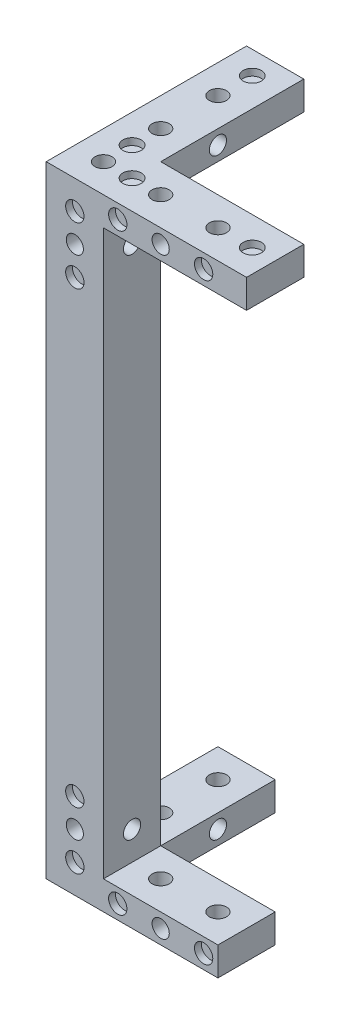
SolidWorks part; units mm, degrees
ref_plane "Front Plane" through (0, 0, 0) normal (0, 0, 1) x (1, 0, 0)
ref_plane "Top Plane" through (0, 0, 0) normal (0, 1, 0) x (1, 0, 0)
ref_plane "Right Plane" through (0, 0, 0) normal (1, 0, 0) x (0, 0, -1)
sketch "Sketch1" plane through (0, 0, 0) normal (0, 1, 0) x (1, 0, 0)
  line L1 (0, 0) -> (30, 0)
  line L2 (0, 0) -> (0, 10)
  line L3 (0, 10) -> (30, 10)
  line L4 (30, 0) -> (30, 10)
  line L5 (0, 0) -> (10, 0)
  line L6 (0, 0) -> (0, 30)
  line L7 (0, 30) -> (10, 30)
  line L8 (10, 0) -> (10, 30)
  dimension "D1" = 10
  dimension "D2" = 10
  dimension "D3" = 30
  dimension "D4" = 30
extrude "Boss-Extrude1" add sketch "Sketch1" along normal blind 10 contours L3 L8 L7 L6 | L1 L8 L3 L2 | L8 L1 L4 L3
sketch "Sketch2" plane through (0, 10, 0) normal (0, 1, 0) x (1, 0, 0)
  line L1 (0, 0) -> (10, 0)
  line L2 (0, 0) -> (0, 10)
  line L3 (0, 10) -> (10, 10)
  line L4 (10, 0) -> (10, 10)
extrude "Boss-Extrude2" add sketch "Sketch2" along normal blind 93.5
sketch "Sketch3" plane through (0, 103.5, 0) normal (0, 1, 0) x (1, 0, 0)
  line L1 (0, 0) -> (30, 0)
  line L2 (0, 0) -> (0, 10)
  line L3 (0, 10) -> (30, 10)
  line L4 (30, 0) -> (30, 10)
  line L5 (0, 0) -> (10, 0)
  line L6 (0, 0) -> (0, 30)
  line L7 (0, 30) -> (10, 30)
  line L8 (10, 0) -> (10, 30)
  line M9 (0, 10) -> (0, 0)
  line M10 (0, 0) -> (10, 0)
  line M11 (10, 0) -> (10, 10)
  line M12 (10, 10) -> (0, 10)
  dimension "D1" = 10
  dimension "D2" = 30
  dimension "D3" = 10
  dimension "D4" = 30
extrude "Boss-Extrude3" add sketch "Sketch3" along normal blind 5 contours L8 L7 L6 M12 | M12 M9 M10 M11 | L1 L4 L3 M11
sketch "Sketch4" plane through (0, 10, 0) normal (0, 1, 0) x (1, 0, 0)
  line L1 (30, 10) -> (10, 10)
  line L2 (30, 10) -> (30, 0)
  line L3 (30, 0) -> (10, 0)
  line L4 (10, 10) -> (10, 0)
  line L5 (10, 30) -> (0, 30)
  line L6 (10, 30) -> (10, 10)
  line L7 (10, 10) -> (0, 10)
  line L8 (0, 30) -> (0, 10)
extrude "Cut-Extrude1" cut sketch "Sketch4" against normal blind 5 contours L5 L8 L7 L6
sketch "Sketch5" plane through (0, 0, 0) normal (0, 0, 1) x (1, 0, 0)
  line L0 (10, 103.5) -> (10, 5) construction
  line L1 (0, 0) -> (30, 0) construction
  line L2 (10, 5) -> (30, 5) construction
  line L3 (30, 5) -> (30, 0) construction
  line L4 (0, 108.5) -> (0, 0) construction
  line L5 (0, 108.5) -> (0, 0)
  line L6 (0, 54.25) -> (10, 54.25)
  circle A0 centre (5, 5) radius 1.6
  circle A1 centre (27.5, 2.5) radius 1.6
  circle A2 centre (5, 15) radius 1.6
  circle A3 centre (12.5, 2.5) radius 1.6
  circle A4 centre (27.5, 106) radius 1.6
  circle A5 centre (12.5, 106) radius 1.6
  circle A6 centre (5, 103.5) radius 1.6
  circle A7 centre (5, 93.5) radius 1.6
  dimension "D1" = 3.2
  dimension "D2" = 5
  dimension "D3" = 5
  dimension "D4" = 3.2
  dimension "D5" = 2.5
  dimension "D6" = 2.5
  dimension "D7" = 2.5
  dimension "D8" = 3.2
  dimension "D9" = 5
  dimension "D10" = 10
  dimension "D11" = 3.2
  dimension "D12" = 15
extrude "Cut-Extrude2" cut sketch "Sketch5" against normal blind 1.2 contours A4 | A5 | A6 | A7 | A2 | A0 | A3 | A1
sketch "Sketch6" plane through (0, 0, 0) normal (0, 0, 1) x (1, 0, 0)
  line L0 (10, 103.5) -> (30, 103.5) construction
  line L1 (10, 103.5) -> (10, 5) construction
  line L2 (0, 108.5) -> (0, 0)
  line L3 (0, 54.25) -> (10, 54.25)
  circle A0 centre (5, 98.5) radius 1.5
  circle A1 centre (20, 106) radius 1.5
  circle A2 centre (5, 103.5) radius 1.6 construction
  circle A4 centre (20, 2.5) radius 1.5
  circle A5 centre (5, 10) radius 1.5
  circle A6 centre (27.5, 106) radius 1.6 construction
  circle A7 centre (12.5, 106) radius 1.6 construction
  dimension "D1" = 3
  dimension "D2" = 2.5
  dimension "D3" = 5
  dimension "D4" = 3
  dimension "D5" = 5
  dimension "D6" = 7.5
  dimension "D7" = 7.5
extrude "Cut-Extrude3" cut sketch "Sketch6" against normal blind 10 contours A1 | A0 | A5 | A4
sketch "Sketch7" plane through (0, 0, 0) normal (-1, 0, 0) x (0, 0, 1)
  line L0 (0, 108.5) -> (-30, 108.5) construction
  line L1 (0, 108.5) -> (0, 0) construction
  line L5 (-30, 108.5) -> (-30, 103.5) construction
  line L8 (0, 108.5) -> (0, 0)
  line L9 (0, 54.25) -> (-10, 54.25)
  line L10 (-10, 103.5) -> (-10, 5) construction
  circle A0 centre (-27.5, 106) radius 1.6
  circle A1 centre (-12.5, 106) radius 1.6
  circle A2 centre (-5, 103.5) radius 1.6
  circle A3 centre (-5, 93.5) radius 1.6
  circle A4 centre (-5, 15) radius 1.6
  circle A5 centre (-5, 5) radius 1.6
  circle A6 centre (-12.5, 2.5) radius 1.6
  circle A7 centre (-27.5, 2.5) radius 1.6
  dimension "D1" = 3.2
  dimension "D2" = 3.2
  dimension "D3" = 3.2
  dimension "D4" = 3.2
  dimension "D5" = 2.5
  dimension "D6" = 2.5
  dimension "D7" = 5
  dimension "D8" = 5
  dimension "D9" = 2.5
  dimension "D10" = 15
  dimension "D11" = 5
  dimension "D12" = 10
extrude "Cut-Extrude4" cut sketch "Sketch7" against normal blind 1.2 contours A0 | A1 | A2 | A3 | A7 | A6 | A5 | A4
sketch "Sketch8" plane through (0, 0, 0) normal (-1, 0, 0) x (0, 0, 1)
  line L0 (0, 108.5) -> (-30, 108.5) construction
  line L1 (0, 108.5) -> (0, 0) construction
  line L2 (-30, 108.5) -> (-30, 103.5) construction
  line L3 (0, 108.5) -> (0, 0)
  line L4 (0, 54.25) -> (-10, 54.25)
  line L5 (-10, 103.5) -> (-10, 5) construction
  circle A0 centre (-20, 106) radius 1.5
  circle A1 centre (-5, 98.5) radius 1.5
  circle A2 centre (-5, 103.5) radius 1.6 construction
  circle A3 centre (-5, 10) radius 1.5
  circle A4 centre (-20, 2.5) radius 1.5
  dimension "D1" = 3
  dimension "D2" = 3
  dimension "D3" = 2.5
  dimension "D4" = 5
  dimension "D5" = 5
  dimension "D6" = 10
extrude "Cut-Extrude5" cut sketch "Sketch8" against normal blind 10.2 contours A4 | A3 | A0 | A1
sketch "Sketch9" plane through (0, 5, 0) normal (0, 1, 0) x (1, 0, 0)
  circle A0 centre (25, 5) radius 1.5 construction
  circle A1 centre (15, 5) radius 1.5 construction
  circle A2 centre (25, 5) radius 1.5
  circle A3 centre (15, 5) radius 1.5
  circle A4 centre (5, 15) radius 1.5 construction
  circle A5 centre (5, 25) radius 1.5 construction
  circle A6 centre (5, 15) radius 1.5
  circle A7 centre (5, 25) radius 1.5
extrude "Cut-Extrude6" cut sketch "Sketch9" against normal blind 10.2
sketch "Sketch10" plane through (0, 0, 0) normal (0, -1, 0) x (1, 0, 0)
  circle A0 centre (5, -5) radius 1.5 construction
  circle A1 centre (5, -5) radius 1.5
extrude "Cut-Extrude7" cut sketch "Sketch10" against normal blind 12.2
sketch "Sketch11" plane through (0, 108.5, 0) normal (0, 1, 0) x (1, 0, 0)
  circle A0 centre (5, 15) radius 1.5 construction
  circle A1 centre (5, 25) radius 1.5 construction
  circle A2 centre (15, 5) radius 1.5 construction
  circle A3 centre (25, 5) radius 1.5 construction
  circle A4 centre (5, 15) radius 1.5
  circle A5 centre (5, 25) radius 1.5
  circle A6 centre (15, 5) radius 1.5
  circle A7 centre (25, 5) radius 1.5
extrude "Cut-Extrude8" cut sketch "Sketch11" against normal blind 10
sketch "Sketch12" plane through (0, 108.5, 0) normal (0, 1, 0) x (1, 0, 0)
  circle A0 centre (5, 5) radius 1.5 construction
  circle A1 centre (5, 5) radius 1.5
extrude "Cut-Extrude9" cut sketch "Sketch12" against normal blind 12
sketch "Sketch13" plane through (0, 108.5, 0) normal (0, 1, 0) x (1, 0, 0)
  line L1 (0, 0) -> (30, 0) construction
  line L2 (0, 0) -> (0, 30) construction
  circle A1 centre (10, 5) radius 1.6
  circle A2 centre (5, 10) radius 1.6
  circle A6 centre (5, 15) radius 1.5 construction
  circle A8 centre (15, 5) radius 1.5 construction
  dimension "D2" = 3.2
  dimension "D4" = 3.2
  dimension "D7" = 5
  dimension "D8" = 5
  dimension "D10" = 5
  dimension "D11" = 5
extrude "Cut-Extrude10" cut sketch "Sketch13" against normal blind 1.2
sketch "Sketch14" plane through (0, 0, -30) normal (0, 0, -1) x (-1, 0, 0)
  line L4 (-10, 103.5) -> (0, 103.5)
  line L5 (0, 103.5) -> (0, 108.5)
  line L6 (0, 108.5) -> (-10, 108.5)
  line L7 (-10, 108.5) -> (-10, 103.5)
  line L8 (-10, 103.5) -> (0, 103.5)
  line L9 (0, 103.5) -> (0, 108.5)
  line L10 (0, 108.5) -> (-10, 108.5)
  line L11 (-10, 108.5) -> (-10, 103.5)
  dimension "D1" = 0
extrude "Boss-Extrude4" add sketch "Sketch14" along normal blind 5
sketch "Sketch15" plane through (30, 0, 0) normal (1, 0, 0) x (0, 0, -1)
  line L4 (0, 103.5) -> (10, 103.5)
  line L5 (10, 103.5) -> (10, 108.5)
  line L6 (10, 108.5) -> (0, 108.5)
  line L7 (0, 108.5) -> (0, 103.5)
  line L8 (0, 103.5) -> (10, 103.5)
  line L9 (10, 103.5) -> (10, 108.5)
  line L10 (10, 108.5) -> (0, 108.5)
  line L11 (0, 108.5) -> (0, 103.5)
  dimension "D1" = 0
extrude "Boss-Extrude5" add sketch "Sketch15" along normal blind 5
sketch "Sketch16" plane through (0, 108.5, 0) normal (0, 1, 0) x (1, 0, 0)
  line L0 (0, 0) -> (35, 0) construction
  line L1 (0, 0) -> (0, 35) construction
  line L2 (35, 10) -> (35, 0) construction
  line L3 (0, 35) -> (10, 35) construction
  circle A0 centre (31, 5) radius 1.6
  circle A1 centre (5, 31) radius 1.6
  dimension "D1" = 3.2
  dimension "D2" = 3.2
  dimension "D3" = 5
  dimension "D4" = 5
  dimension "D5" = 4
  dimension "D6" = 4
extrude "Cut-Extrude11" cut sketch "Sketch16" against normal up to surface (1.2 mm away) up to face at (5, 107.3, -8.4)
